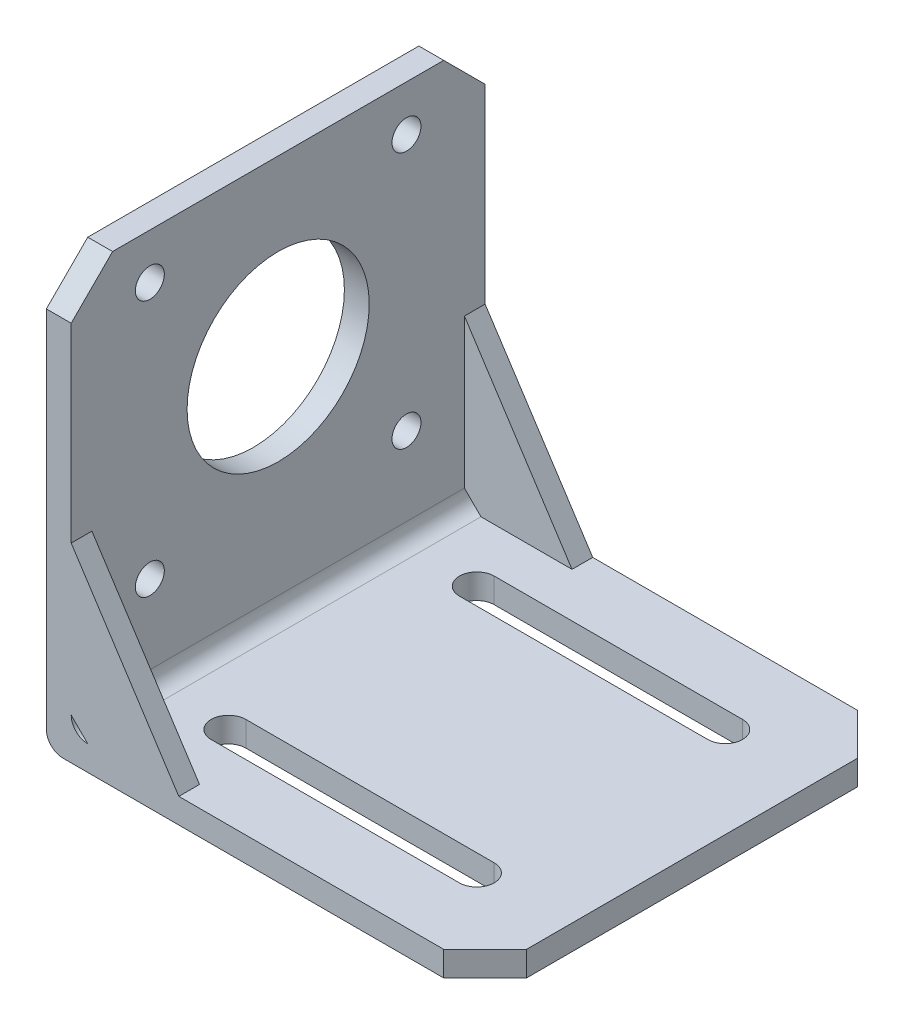
SolidWorks part; units mm, degrees
ref_plane "前视基准面" through (0, 0, 0) normal (0, 0, 1) x (1, 0, 0)
ref_plane "上视基准面" through (0, 0, 0) normal (0, 1, 0) x (1, 0, 0)
ref_plane "右视基准面" through (0, 0, 0) normal (1, 0, 0) x (0, 0, -1)
sketch "草图1" plane through (0, 0, 0) normal (0, 0, 1) x (1, 0, 0)
  line L0 (0, 0) -> (-53, 0)
  line L1 (-53, 0) -> (-53, 51)
  line L2 (-53, 51) -> (-50, 51)
  line L3 (-50, 51) -> (-50, 3)
  line L4 (-50, 3) -> (0, 3)
  line L5 (0, 3) -> (0, 0)
  dimension "D1" = 53
  dimension "D2" = 51
  dimension "D3" = 3
  dimension "D4" = 3
extrude "凸台-拉伸1" add sketch "草图1" along normal mid plane 50
sketch "草图2" plane through (-50, 0, 0) normal (1, 0, 0) x (0, 0, -1)
  line L0 (0, -1000) -> (0, 49000) construction
  line L1 (-25, 51) -> (25, 51) construction
  line L2 (-1000, 30) -> (49000, 30) construction
  circle A0 centre (0, 30) radius 11
  circle A1 centre (-15.5, 45.5) radius 1.75
  circle A2 centre (15.5, 45.5) radius 1.75
  circle A3 centre (-15.5, 14.5) radius 1.75
  circle A4 centre (15.5, 14.5) radius 1.75
  dimension "D1" = 22
  dimension "D3" = 3.5
  dimension "D2" = 21
  dimension "D4" = 31
  dimension "D5" = 31
extrude "切除-拉伸1" cut sketch "草图2" against normal up to next
sketch "草图3" plane through (0, 3, 0) normal (0, 1, 0) x (1, 0, 0)
  line L0 (-1000, 0) -> (49000, 0) construction
  line L1 (-41, 15) -> (-11, 15) construction
  line L2 (-41, 17.1) -> (-11, 17.1)
  line L3 (-41, 12.9) -> (-11, 12.9)
  line L4 (-41, -15) -> (-11, -15) construction
  line L5 (-41, -12.9) -> (-11, -12.9)
  line L6 (-41, -17.1) -> (-11, -17.1)
  line L7 (0, -25) -> (0, 25) construction
  arc A0 (-41, 17.1) -> (-41, 12.9) centre (-41, 15) ccw
  arc A1 (-11, 12.9) -> (-11, 17.1) centre (-11, 15) ccw
  arc A2 (-41, -12.9) -> (-41, -17.1) centre (-41, -15) ccw
  arc A3 (-11, -17.1) -> (-11, -12.9) centre (-11, -15) ccw
  point P5 (-26, 15)
  point P10 (-26, -15)
  dimension "D4" = 2.1
  dimension "D1" = 30
  dimension "D2" = 30
  dimension "D3" = 11
extrude "切除-拉伸2" cut sketch "草图3" against normal up to next
chamfer "倒角1" distance 5 angle 45 4 edges at (0, 1.5, -25) (0, 1.5, 25) (-51.5, 51, -25) (-51.5, 51, 25)
fillet "圆角1" radius 2 2 edges at (-53, 0, 0) (-50, 3, 0)
sketch "草图4" plane through (0, 0, 25) normal (0, 0, 1) x (1, 0, 0)
  line L0 (-50, 23) -> (-50, 5)
  line L1 (-50, 5) -> (-50, 46) construction
  line L2 (-50, 5) -> (-48, 3)
  line L3 (-5, 3) -> (-48, 3) construction
  line L4 (-48, 3) -> (-37, 3)
  line L5 (-37, 3) -> (-50, 23)
  dimension "D1" = 13
  dimension "D2" = 20
  dimension "D3" = 2
  dimension "D4" = 2
extrude "凸台-拉伸2" add sketch "草图4" against normal blind 2.5
mirror "镜向1" about plane through (0, 0, 0) normal (0, 0, 1) of "凸台-拉伸2"
